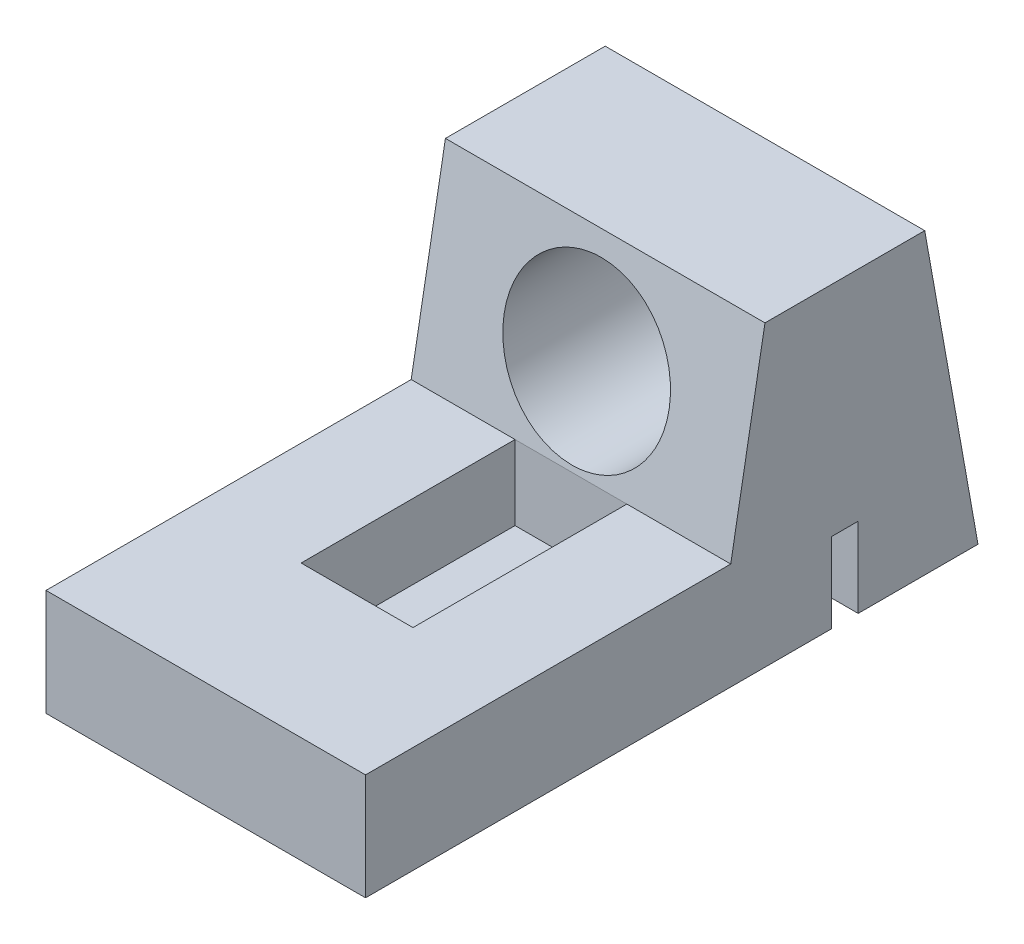
SolidWorks part; units mm, degrees
ref_plane "정면" through (0, 0, 0) normal (0, 0, 1) x (1, 0, 0)
ref_plane "윗면" through (0, 0, 0) normal (0, 1, 0) x (1, 0, 0)
ref_plane "우측면" through (0, 0, 0) normal (1, 0, 0) x (0, 0, -1)
sketch "스케치3" plane through (0, 0, 0) normal (1, 0, 0) x (0, 0, -1)
  line L0 (0, 4.5456) -> (0, -51.4544) construction
  line L1 (-25, -51.4544) -> (25, -51.4544)
  line L2 (-15, 4.5456) -> (15, 4.5456)
  line L3 (-15, 4.5456) -> (-25, -51.4544)
  line L4 (15, 4.5456) -> (25, -51.4544)
  dimension "D2" = 50
  dimension "D3" = 30
  dimension "D4" = 56
extrude "보스-돌출1" add sketch "스케치3" along normal blind 60
sketch "스케치4" plane through (0, 0, 0) normal (0, 0, 1) x (1, 0, 0)
  line L0 (-1.9678, -14.9544) -> (61.9678, -14.9544) construction
  line L1 (30, -51.4544) -> (30, 7.4262) construction
  line L2 (60, -51.4544) -> (0, -51.4544) construction
  circle A0 centre (30, -14.9544) radius 15.5
  dimension "D1" = 31
  dimension "D2" = 21
extrude "컷-돌출1" cut sketch "스케치4" along normal blind 40 and the other way blind 29
sketch "스케치5" plane through (0, 0, 0) normal (1, 0, 0) x (0, 0, -1)
  line L0 (0, 7.2507) -> (0, -19.0866) construction
  line L1 (-25, -51.4544) -> (25, -51.4544) construction
  line L2 (2.5, -66.4544) -> (-2.5, -66.4544)
  line L3 (2.5, -66.4544) -> (2.5, -36.4544)
  line L4 (2.5, -36.4544) -> (-2.5, -36.4544)
  line L5 (-2.5, -66.4544) -> (-2.5, -36.4544)
  line L6 (2.5, -66.4544) -> (-2.5, -36.4544) construction
  line L7 (2.5, -36.4544) -> (-2.5, -66.4544) construction
  point P3 (0, -51.4544)
  dimension "D1" = 5
  dimension "D2" = 30
extrude "컷-돌출2" cut sketch "스케치5" along normal through all
ref_plane "평면1" through (0, -51.4544, 0) normal (0, -1, 0) x (-1, 0, 0)
sketch "스케치7" plane through (0, -51.4544, 0) normal (0, -1, 0) x (-1, 0, 0)
  line L0 (-60, -25) -> (-60, -2.5) construction
  line L1 (-60, -4.5751) -> (0, -4.5751)
  line L2 (-60, -4.5751) -> (-60, -90)
  line L3 (-60, -90) -> (0, -90)
  line L4 (0, -4.5751) -> (0, -90)
  line L5 (-60, -25) -> (0, -25) construction
  dimension "D1" = 65
extrude "보스-돌출2" add sketch "스케치7" against normal blind 20
sketch "스케치9" plane through (0, 0, 0) normal (0, 1, 0) x (1, 0, 0)
  line L0 (30, 25) -> (30, -98.3142) construction
  line L1 (19.5, -21.4286) -> (40.5, -21.4286)
  line L2 (19.5, -21.4286) -> (19.5, -61.5986)
  line L3 (19.5, -61.5986) -> (40.5, -61.5986)
  line L4 (40.5, -21.4286) -> (40.5, -61.5986)
  line L5 (60, 25) -> (0, 25) construction
  line L6 (60, -21.4286) -> (0, -21.4286) construction
  dimension "D1" = 40.17
  dimension "D2" = 10.5
  dimension "D3" = 10.5
extrude "컷-돌출3" cut sketch "스케치9" against normal blind 14 from surface at -31.4544 starting at face at (30, -31.4544, 55.7143)
